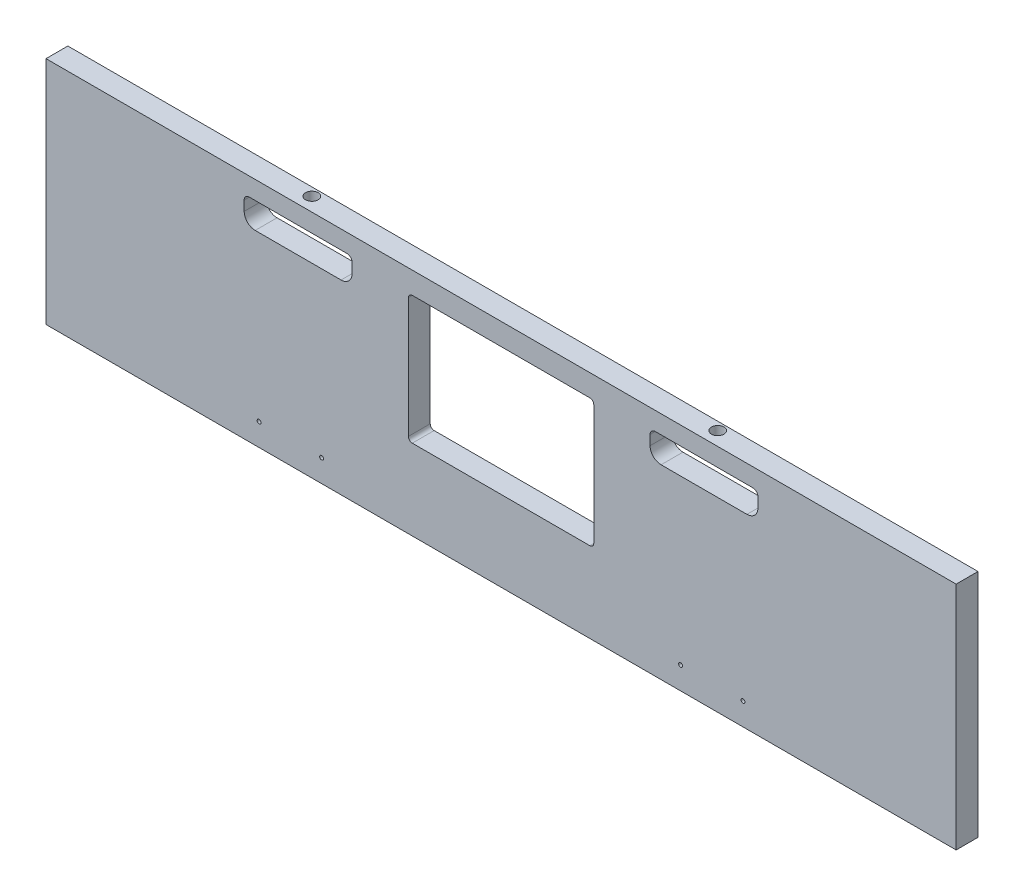
SolidWorks part; units mm, degrees
material "Pine"
ref_plane "Front Plane" through (0, 0, 0) normal (0, 0, 1) x (1, 0, 0)
ref_plane "Top Plane" through (0, 0, 0) normal (0, 1, 0) x (1, 0, 0)
ref_plane "Right Plane" through (0, 0, 0) normal (1, 0, 0) x (0, 0, -1)
sketch "Sketch1" plane through (0, 0, 0) normal (0, 0, 1) x (1, 0, 0)
  line L0 (-163.9887, -5335.905) -> (-163.9887, -5432.425)
  line L1 (-102.87, -5350.891) -> (-33.02, -5350.891)
  line L2 (-111.8235, -5341.9375) -> (-111.8235, -5334)
  line L3 (-24.0665, -5341.9375) -> (-24.0665, -5334)
  line L4 (-298.9262, -5332.73) -> (-167.1637, -5332.73)
  line L5 (-167.1637, -5435.6) -> (-298.9262, -5435.6)
  line L6 (-302.1012, -5432.425) -> (-302.1012, -5335.905)
  line L7 (-107.6325, -5329.809) -> (-28.2575, -5329.809)
  line L8 (174.9425, -5308.6) -> (174.9425, -5581.65)
  line L9 (449.2625, -5413.1661) -> (449.2625, -5421.9659)
  line L10 (595.3125, -5421.9659) -> (595.3125, -5413.1661)
  line L11 (839.47, -5509.5521) -> (839.47, -5307.6729)
  line L12 (839.47, -5307.6729) -> (863.6, -5307.6729)
  line L13 (839.47, -5509.5521) -> (863.6, -5509.5521)
  line L14 (863.6, -5509.5521) -> (863.6, -5307.6729)
  line L15 (-354.2665, -5341.9375) -> (-354.2665, -5334)
  line L16 (-100.8856, -5889.625) -> (-50.0856, -5889.625)
  line L17 (-104.0606, -5969) -> (-104.0606, -5892.8)
  line L18 (-46.9106, -5892.8) -> (-46.9106, -5969)
  line L19 (-50.0856, -5972.175) -> (-100.8856, -5972.175)
  line L20 (-100.8856, -5848.35) -> (-50.0856, -5848.35)
  line L21 (857.25, -5502.275) -> (157.1625, -5575.3)
  line L22 (857.25, -5314.95) -> (857.25, -5502.275)
  line L23 (157.1625, -5314.95) -> (157.1625, -5575.3)
  line L24 (857.25, -5314.95) -> (157.1625, -5314.95)
  line L25 (150.8125, -5308.6) -> (174.9425, -5308.6)
  line L26 (174.9425, -5581.65) -> (150.8125, -5581.65)
  line L27 (137.16, -5314.95) -> (137.16, -5502.275)
  line L28 (150.8125, -5581.65) -> (150.8125, -5308.6)
  line L29 (590.8224, -5408.676) -> (453.7526, -5408.676)
  line L30 (453.7526, -5426.456) -> (590.8224, -5426.456)
  line L31 (137.16, -6013.45) -> (137.16, -5867.4)
  line L32 (150.8125, -5746.75) -> (150.8125, -6019.8)
  line L33 (143.51, -5639.9938) -> (143.51, -5654.294)
  line L34 (590.8224, -5919.724) -> (453.7526, -5919.724)
  line L35 (453.7526, -5901.944) -> (590.8224, -5901.944)
  line L36 (449.2625, -5915.2339) -> (449.2625, -5906.4341)
  line L37 (174.9425, -6019.8) -> (174.9425, -5746.75)
  line L38 (595.3125, -5906.4341) -> (595.3125, -5915.2339)
  line L39 (839.47, -5818.8479) -> (839.47, -6020.7271)
  line L40 (839.47, -5818.8479) -> (863.6, -5818.8479)
  line L41 (863.6, -5818.8479) -> (863.6, -6020.7271)
  line L42 (839.47, -6020.7271) -> (863.6, -6020.7271)
  line L43 (-155.8782, -5867.4) -> (-603.25, -5867.4)
  line L44 (-433.07, -5350.891) -> (-363.22, -5350.891)
  line L45 (-437.8325, -5329.809) -> (-358.4575, -5329.809)
  line L46 (889, -6045.2) -> (-635, -6045.2)
  line L47 (-635, -5283.2) -> (889, -5283.2)
  line L48 (-635, -6045.2) -> (-635, -5283.2)
  line L49 (889, -5283.2) -> (889, -6045.2)
  line L50 (137.16, -5502.275) -> (-603.25, -5502.275)
  line L51 (-603.25, -5314.95) -> (137.16, -5314.95)
  line L52 (143.51, -5654.294) -> (-609.6, -5654.294)
  line L53 (-609.6, -5639.9938) -> (143.51, -5639.9938)
  line L54 (137.16, -5536.0062) -> (-603.25, -5536.0062)
  line L55 (-603.25, -5794.375) -> (137.16, -5794.375)
  line L56 (-603.25, -6013.45) -> (137.16, -6013.45)
  line L57 (-603.25, -5536.0062) -> (-603.25, -5794.375)
  line L58 (137.16, -5794.375) -> (137.16, -5536.0062)
  line L59 (-609.6, -5654.294) -> (-609.6, -5639.9938)
  line L60 (-603.25, -5867.4) -> (-603.25, -6013.45)
  line L61 (-603.25, -5314.95) -> (-603.25, -5502.275)
  line L62 (-442.0235, -5341.9375) -> (-442.0235, -5334)
  line L63 (857.25, -5826.125) -> (157.1625, -5753.1)
  line L64 (857.25, -6013.45) -> (857.25, -5826.125)
  line L65 (157.1625, -6013.45) -> (157.1625, -5753.1)
  line L66 (857.25, -6013.45) -> (157.1625, -6013.45)
  line L67 (174.9425, -5746.75) -> (150.8125, -5746.75)
  line L68 (150.8125, -6019.8) -> (174.9425, -6019.8)
  line L69 (137.16, -5867.4) -> (4.907, -5867.4)
  circle A0 centre (-36.195, -5484.0124) radius 1.5875
  arc A1 (-298.9262, -5332.73) -> (-302.1012, -5335.905) centre (-298.9262, -5335.905) ccw
  arc A2 (-302.1012, -5432.425) -> (-298.9262, -5435.6) centre (-298.9262, -5432.425) ccw
  arc A3 (-163.9887, -5335.905) -> (-167.1637, -5332.73) centre (-167.1637, -5335.905) ccw
  arc A4 (-167.1637, -5435.6) -> (-163.9887, -5432.425) centre (-167.1637, -5432.425) ccw
  arc A5 (-111.8235, -5341.9375) -> (-102.87, -5350.891) centre (-102.87, -5341.9375) ccw
  arc A6 (-107.6325, -5329.809) -> (-111.8235, -5334) centre (-107.6325, -5334) ccw
  circle A7 centre (166.0525, -5444.6613) radius 1.5875
  circle A8 centre (166.0525, -5358.1871) radius 1.5875
  circle A9 centre (471.4875, -5417.566) radius 1.5875
  arc A10 (453.7526, -5408.676) -> (449.2625, -5413.1661) centre (451.5076, -5410.9211) ccw
  arc A11 (449.2625, -5421.9659) -> (453.7526, -5426.456) centre (451.5076, -5424.2109) ccw
  circle A12 centre (522.2875, -5417.566) radius 1.5875
  circle A13 centre (573.0875, -5417.566) radius 1.5875
  arc A14 (590.8224, -5426.456) -> (595.3125, -5421.9659) centre (593.0674, -5424.2109) ccw
  arc A15 (595.3125, -5413.1661) -> (590.8224, -5408.676) centre (593.0674, -5410.9211) ccw
  circle A16 centre (848.36, -5471.8269) radius 1.5875
  circle A17 centre (848.36, -5409.0762) radius 1.5875
  circle A18 centre (848.36, -5346.3254) radius 1.5875
  arc A19 (-363.22, -5350.891) -> (-354.2665, -5341.9375) centre (-363.22, -5341.9375) ccw
  arc A20 (-354.2665, -5334) -> (-358.4575, -5329.809) centre (-358.4575, -5334) ccw
  arc A21 (-24.0665, -5334) -> (-28.2575, -5329.809) centre (-28.2575, -5334) ccw
  arc A22 (-33.02, -5350.891) -> (-24.0665, -5341.9375) centre (-33.02, -5341.9375) ccw
  circle A23 centre (-86.995, -5484.0124) radius 1.5875
  circle A24 centre (-333.4544, -5894.07) radius 2.54
  circle A25 centre (-333.4544, -5994.4) radius 2.54
  arc A26 (-104.0606, -5969) -> (-100.8856, -5972.175) centre (-100.8856, -5969) ccw
  arc A27 (-50.0856, -5972.175) -> (-46.9106, -5969) centre (-50.0856, -5969) ccw
  arc A28 (-100.8856, -5848.35) -> (-128.3819, -5857.875) centre (-100.8856, -5892.8) ccw
  arc A29 (-155.8782, -5867.4) -> (-128.3819, -5857.875) centre (-155.8782, -5822.95) ccw
  arc A30 (-22.5893, -5857.875) -> (-50.0856, -5848.35) centre (-50.0856, -5892.8) ccw
  circle A31 centre (-132.6356, -5894.07) radius 2.54
  circle A32 centre (-132.6356, -5994.4) radius 2.54
  arc A33 (-46.9106, -5892.8) -> (-50.0856, -5889.625) centre (-50.0856, -5892.8) ccw
  arc A34 (-100.8856, -5889.625) -> (-104.0606, -5892.8) centre (-100.8856, -5892.8) ccw
  arc A35 (-22.5893, -5857.875) -> (4.907, -5867.4) centre (4.907, -5822.95) ccw
  circle A36 centre (166.0525, -5531.1356) radius 1.5875
  arc A37 (449.2625, -5915.2339) -> (453.7526, -5919.724) centre (451.5076, -5917.4789) ccw
  arc A38 (453.7526, -5901.944) -> (449.2625, -5906.4341) centre (451.5076, -5904.1891) ccw
  circle A39 centre (166.0525, -5797.2644) radius 1.5875
  circle A40 centre (166.0525, -5883.7387) radius 1.5875
  circle A41 centre (166.0525, -5970.2129) radius 1.5875
  circle A42 centre (471.4875, -5910.834) radius 1.5875
  circle A43 centre (522.2875, -5910.834) radius 1.5875
  circle A44 centre (573.0875, -5910.834) radius 1.5875
  arc A45 (595.3125, -5906.4341) -> (590.8224, -5901.944) centre (593.0674, -5904.1891) ccw
  arc A46 (590.8224, -5919.724) -> (595.3125, -5915.2339) centre (593.0674, -5917.4789) ccw
  circle A47 centre (848.36, -5919.3238) radius 1.5875
  circle A48 centre (848.36, -5982.0746) radius 1.5875
  circle A49 centre (848.36, -5856.5731) radius 1.5875
  arc A50 (-437.8325, -5329.809) -> (-442.0235, -5334) centre (-437.8325, -5334) ccw
  circle A51 centre (-429.895, -5484.0124) radius 1.5875
  arc A52 (-442.0235, -5341.9375) -> (-433.07, -5350.891) centre (-433.07, -5341.9375) ccw
  circle A53 centre (-379.095, -5484.0124) radius 1.5875
sketch "Sketch2" plane through (0, 0, 0) normal (0, 0, 1) x (1, 0, 0)
  line L0 (137.16, -5502.275) -> (137.16, -5314.95)
  line L1 (137.16, -5314.95) -> (-603.25, -5314.95)
  line L2 (-603.25, -5314.95) -> (-603.25, -5502.275)
  line L3 (-603.25, -5502.275) -> (137.16, -5502.275)
extrude "Extrude1" add sketch "Sketch2" against normal blind 17.78
sketch "Sketch3" plane through (0, 0, 0) normal (0, 0, 1) x (1, 0, 0)
  line L0 (-308.4512, -5335.905) -> (-308.4512, -5433.695)
  line L1 (-305.2762, -5436.87) -> (-160.8137, -5436.87)
  line L2 (-157.6387, -5433.695) -> (-157.6387, -5335.905)
  line L3 (-160.8137, -5332.73) -> (-305.2762, -5332.73)
  line L4 (-354.2665, -5334) -> (-354.2665, -5341.9375)
  line L5 (-363.22, -5350.891) -> (-433.07, -5350.891)
  line L6 (-442.0235, -5341.9375) -> (-442.0235, -5334)
  line L7 (-437.8325, -5329.809) -> (-358.4575, -5329.809)
  line L8 (-102.87, -5350.891) -> (-33.02, -5350.891)
  line L9 (-24.0665, -5341.9375) -> (-24.0665, -5334)
  line L10 (-28.2575, -5329.809) -> (-107.6325, -5329.809)
  line L11 (-111.8235, -5334) -> (-111.8235, -5341.9375)
  line L12 (-148.1137, -5332.73) -> (-317.9762, -5332.73) construction
  line L16 (-157.6387, -5461.3175) -> (-157.6387, -5332.73) construction
  line L17 (-308.4512, -5332.73) -> (-308.4512, -5461.3175) construction
  line L21 (-385.445, -5436.87) -> (-80.645, -5436.87) construction
  line L22 (-398.145, -5329.809) -> (-398.145, -5314.95) construction
  line L23 (137.16, -5314.95) -> (-603.25, -5314.95) construction
  line L24 (-398.145, -5329.809) -> (-398.145, -5350.891) construction
  arc A0 (-308.4512, -5433.695) -> (-305.2762, -5436.87) centre (-305.2762, -5433.695) ccw
  arc A1 (-160.8137, -5436.87) -> (-157.6387, -5433.695) centre (-160.8137, -5433.695) ccw
  arc A2 (-157.6387, -5335.905) -> (-160.8137, -5332.73) centre (-160.8137, -5335.905) ccw
  arc A3 (-305.2762, -5332.73) -> (-308.4512, -5335.905) centre (-305.2762, -5335.905) ccw
  arc A4 (-354.2665, -5341.9375) -> (-363.22, -5350.891) centre (-363.22, -5341.9375) cw
  arc A5 (-433.07, -5350.891) -> (-442.0235, -5341.9375) centre (-433.07, -5341.9375) cw
  arc A6 (-442.0235, -5334) -> (-437.8325, -5329.809) centre (-437.8325, -5334) cw
  arc A7 (-358.4575, -5329.809) -> (-354.2665, -5334) centre (-358.4575, -5334) cw
  arc A8 (-33.02, -5350.891) -> (-24.0665, -5341.9375) centre (-33.02, -5341.9375) ccw
  arc A9 (-24.0665, -5334) -> (-28.2575, -5329.809) centre (-28.2575, -5334) ccw
  arc A10 (-107.6325, -5329.809) -> (-111.8235, -5334) centre (-107.6325, -5334) ccw
  arc A11 (-111.8235, -5341.9375) -> (-102.87, -5350.891) centre (-102.87, -5341.9375) ccw
  circle A12 centre (-429.895, -5484.0124) radius 1.5875
  circle A13 centre (-379.095, -5484.0124) radius 1.5875
  circle A14 centre (-86.995, -5484.0124) radius 1.5875
  circle A15 centre (-36.195, -5484.0124) radius 1.5875
  point P16 (-509.5773, -5301.4203)
  dimension "D1" = 21.082
  dimension "D2" = 14.859
extrude "Cut-Extrude1" cut sketch "Sketch3" against normal up to surface (17.78 mm away) up to face at (-233.045, -5408.6125, -17.78)
sketch "Sketch4" plane through (0, -5314.95, 0) normal (0, 1, 0) x (1, 0, 0)
  circle A0 centre (-67.97, 11.1873) radius 5.08
  circle A1 centre (-398.17, 11.1873) radius 5.08
extrude "Cut-Extrude2" cut sketch "Sketch4" against normal up to surface (14.859 mm away) up to face at (-67.945, -5329.809, -8.89)
